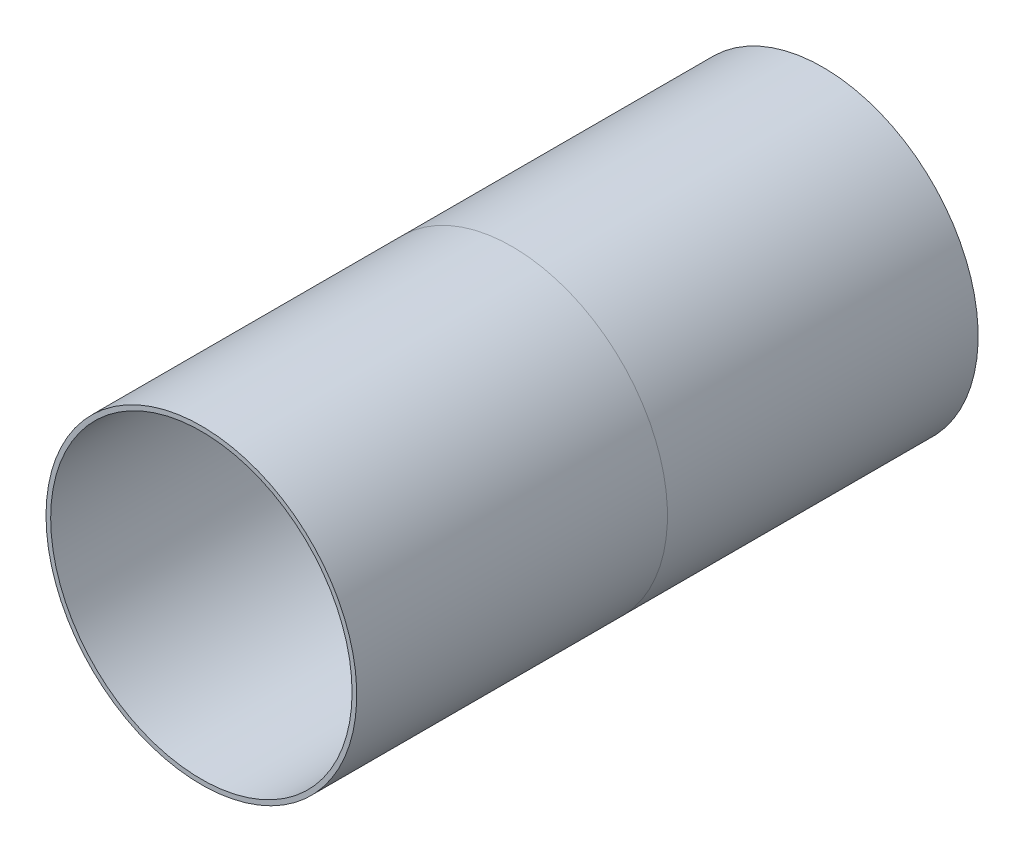
SolidWorks part; units mm, degrees
ref_plane "Plan de face" through (0, 0, 0) normal (0, 0, 1) x (1, 0, 0)
ref_plane "Plan de dessus" through (0, 0, 0) normal (0, 1, 0) x (1, 0, 0)
ref_plane "Plan de droite" through (0, 0, 0) normal (1, 0, 0) x (0, 0, -1)
sketch "Esquisse2" plane through (0, 0, 0) normal (0, 0, 1) x (1, 0, 0)
  circle A0 centre (0, 0) radius 76.1746
  circle A1 centre (0, 0) radius 73.914
  dimension "D1" = 152.3492
  dimension "D2" = 147.828
extrude "Boss.-Extru.1" add sketch "Esquisse2" along normal blind 152.4
sketch "Esquisse3" plane through (0, 0, 152.4) normal (0, 0, 1) x (1, 0, 0)
  circle A0 centre (0, 0) radius 76.2
  circle A1 centre (0, 0) radius 73.914
  dimension "D1" = 147.828
extrude "Boss.-Extru.2" add sketch "Esquisse3" along normal blind 152.4
